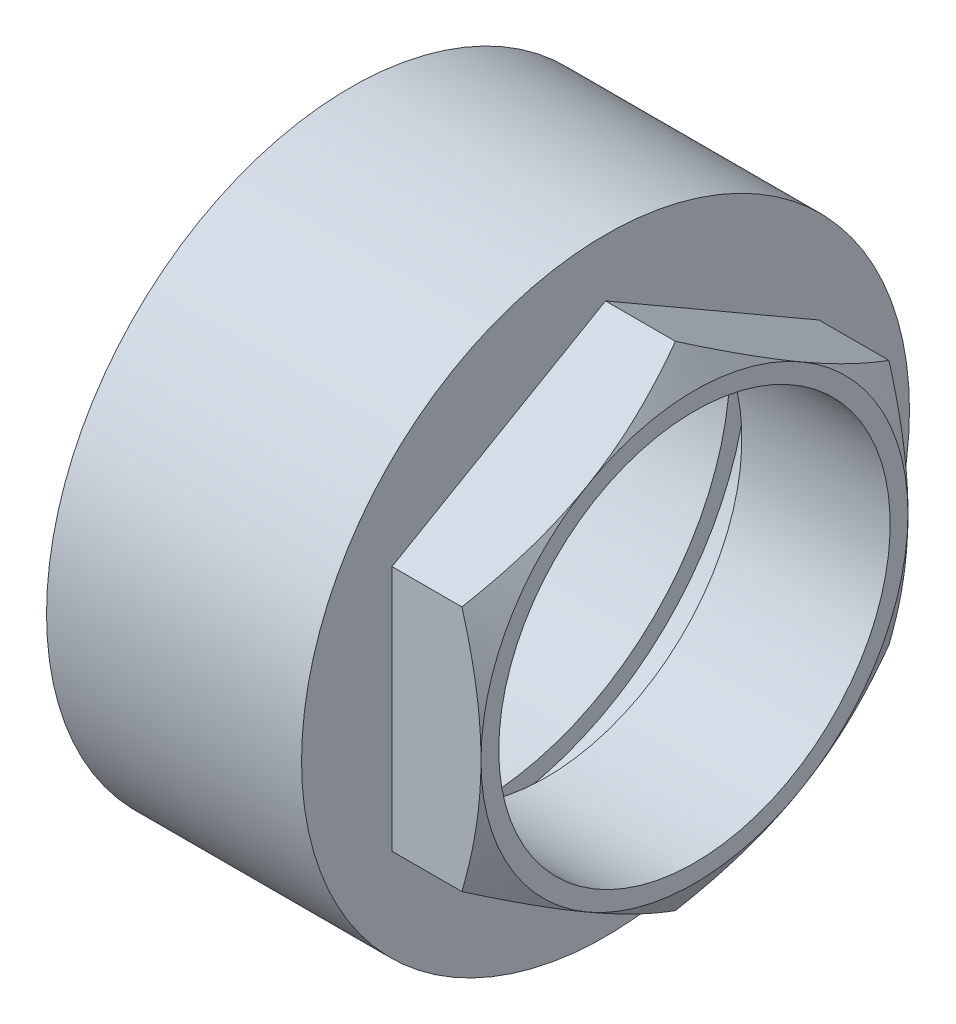
SolidWorks part; units mm, degrees
ref_plane "前基準面" through (0, 0, 0) normal (0, 0, 1) x (1, 0, 0)
ref_plane "上基準面" through (0, 0, 0) normal (0, 1, 0) x (1, 0, 0)
ref_plane "右基準面" through (0, 0, 0) normal (1, 0, 0) x (0, 0, -1)
sketch "草圖2" plane through (0, 0, 0) normal (1, 0, 0) x (0, 0, -1)
  circle A0 centre (0, 0) radius 25.625
  dimension "D1" = 51.25
extrude "伸長1" add sketch "草圖2" along normal blind 21.5
sketch "草圖3" plane through (21.5, 0, 0) normal (1, 0, 0) x (0, 0, -1)
  line L1 (0, 20.7846) -> (-18, 10.3923)
  line L2 (-18, 10.3923) -> (-18, -10.3923)
  line L3 (-18, -10.3923) -> (0, -20.7846)
  line L4 (0, -20.7846) -> (18, -10.3923)
  line L5 (18, -10.3923) -> (18, 10.3923)
  line L6 (18, 10.3923) -> (0, 20.7846)
  circle A0 centre (0, 0) radius 18 construction
  dimension "D1" = 36
extrude "伸長2" add sketch "草圖3" along normal blind 7.5
sketch "草圖4" plane through (0, 0, 0) normal (0, 0, 1) x (1, 0, 0)
  line L0 (0, 0) -> (29.8752, 0) construction
  line L1 (0, 25.625) -> (0, -25.625) construction
  line L2 (27.3923, 20.7846) -> (29, 20.7846)
  line L3 (29, 20.7846) -> (21.5, 20.7846) construction
  line L4 (29, 20.7846) -> (29, 18)
  line L5 (29, 20.7846) -> (29, 10.3923) construction
  line L6 (29, 18) -> (27.3923, 20.7846)
  dimension "D1" = 30
  dimension "D2" = 36
revolve "除料-旋轉1" cut sketch "草圖4" angle 360 about L0
sketch "草圖5" plane through (0, 0, 0) normal (0, 0, 1) x (1, 0, 0)
  line L0 (0, 0) -> (28.0682, 0) construction
  line L1 (0, 0) -> (0, 21.5)
  line L2 (0, 25.625) -> (0, -25.625) construction
  line L3 (0, 21.5) -> (10.5, 21.5)
  line L4 (10.5, 21.5) -> (10.5, 23)
  line L5 (10.5, 23) -> (16.5, 23)
  line L6 (16.5, 23) -> (16.5, 16.5)
  line L7 (16.5, 16.5) -> (29, 16.5)
  line L8 (29, 0) -> (29, 15.5885) construction
  line L9 (29, 16.5) -> (29, 0)
  line L10 (29, 0) -> (0, 0)
  dimension "D1" = 33
  dimension "D2" = 46
  dimension "D3" = 43
  dimension "D4" = 6
  dimension "D5" = 16.5
revolve "除料-旋轉2" cut sketch "草圖5" angle 360 about L0
cosmetic thread "裝飾螺紋線1" parameters "D2"=46
